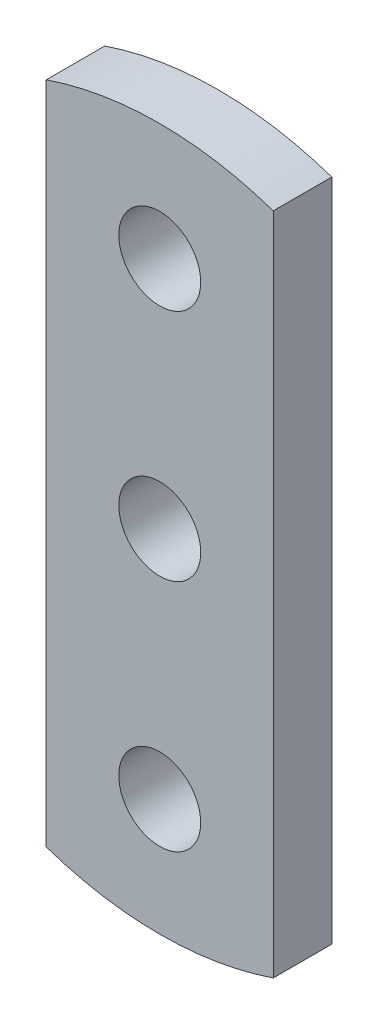
SolidWorks part; units mm, degrees
ref_plane "Alzado" through (0, 0, 0) normal (0, 0, 1) x (1, 0, 0)
ref_plane "Planta" through (0, 0, 0) normal (0, 1, 0) x (1, 0, 0)
ref_plane "Vista lateral" through (0, 0, 0) normal (1, 0, 0) x (0, 0, -1)
sketch "Croquis1" plane through (0, 0, 0) normal (0, 0, 1) x (1, 0, 0)
  line L0 (-4.85, 14.1943) -> (-4.85, -14.1943)
  line L1 (4.85, -14.1943) -> (4.85, 14.1943)
  line L2 (-4.85, 0) -> (4.85, 0) construction
  line L3 (0, 15) -> (0, 10) construction
  line L4 (0, 10) -> (0, 0) construction
  line L5 (0, 0) -> (0, -10) construction
  line L6 (0, -10) -> (0, -15) construction
  arc A0 (4.85, 14.1943) -> (-4.85, 14.1943) centre (0, 0) ccw
  circle A1 centre (0, 10) radius 1.75
  circle A2 centre (0, -10) radius 1.75
  arc A3 (-4.85, -14.1943) -> (4.85, -14.1943) centre (0, 0) ccw
  circle A4 centre (0, 0) radius 1.75
  point P10 (0, 0)
  dimension "D1" = 30
  dimension "D3" = 3.5
  dimension "D2" = 9.7
  dimension "D4" = 5
extrude "Saliente-Extruir1" add sketch "Croquis1" along normal blind 2.5
